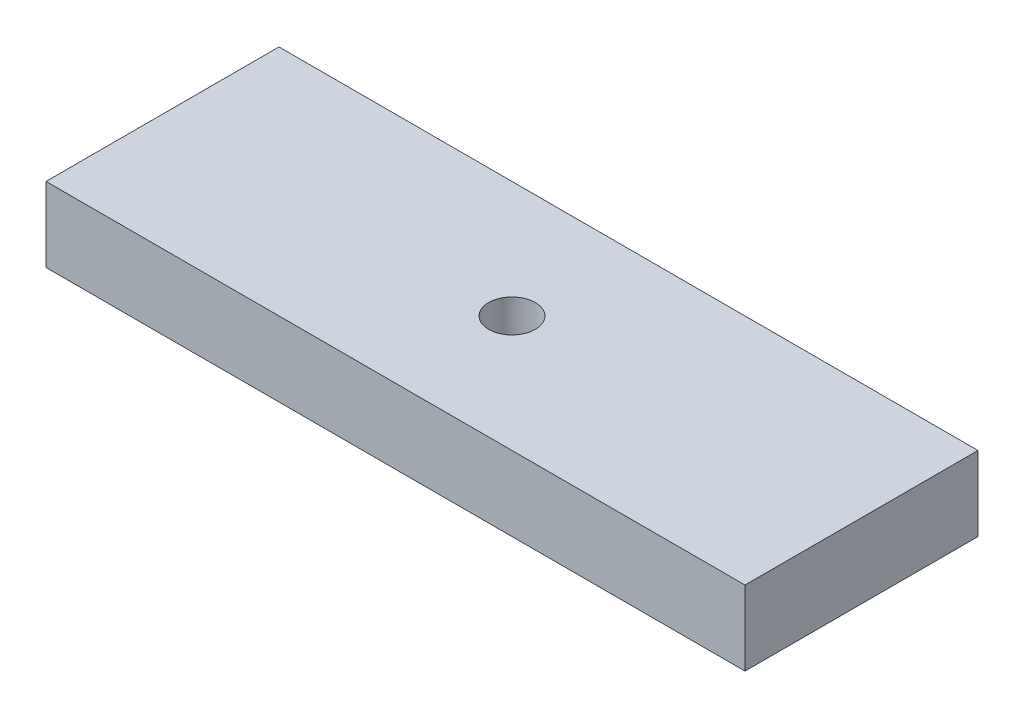
SolidWorks part; units mm, degrees
ref_plane "Alzado" through (0, 0, 0) normal (0, 0, 1) x (1, 0, 0)
ref_plane "Planta" through (0, 0, 0) normal (0, 1, 0) x (1, 0, 0)
ref_plane "Vista lateral" through (0, 0, 0) normal (1, 0, 0) x (0, 0, -1)
sketch "Croquis1" plane through (0, 0, 0) normal (0, 1, 0) x (1, 0, 0)
  line L1 (75, -25) -> (-75, -25)
  line L2 (75, -25) -> (75, 25)
  line L3 (75, 25) -> (-75, 25)
  line L4 (-75, -25) -> (-75, 25)
  line L5 (75, -25) -> (-75, 25) construction
  line L6 (75, 25) -> (-75, -25) construction
  point P0 (0, 0)
  dimension "D1" = 50
  dimension "D2" = 150
extrude "Saliente-Extruir1" add sketch "Croquis1" along normal blind 16
sketch "Croquis2" plane through (0, 16, 0) normal (0, 1, 0) x (1, 0, 0)
  circle A0 centre (0, 0) radius 5
  dimension "D1" = 10
extrude "Cortar-Extruir1" cut sketch "Croquis2" against normal through all
